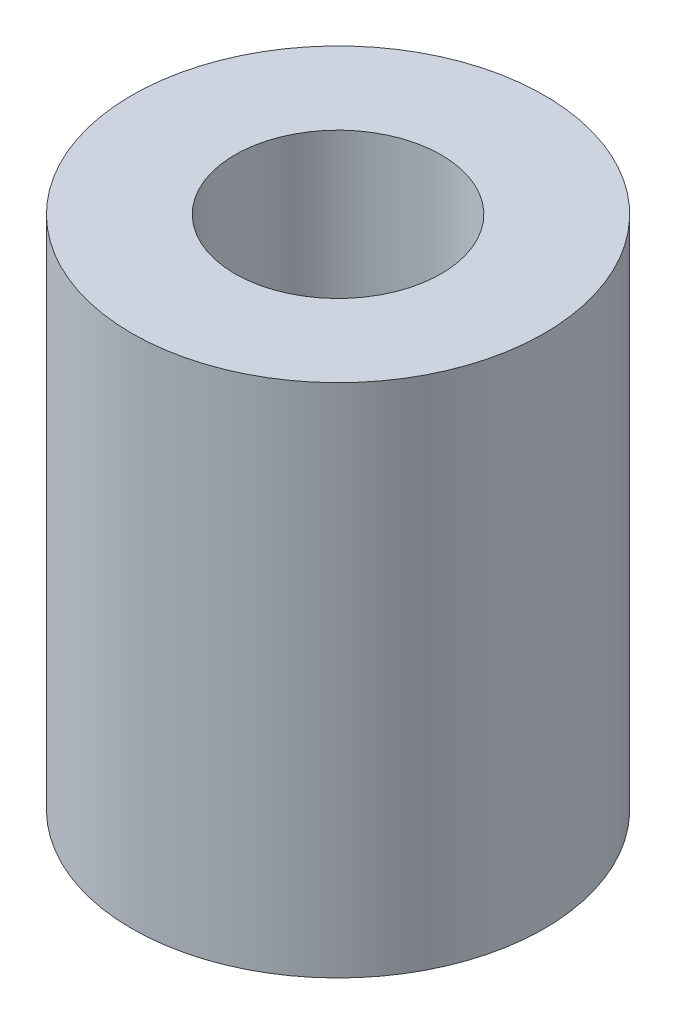
SolidWorks part; units mm, degrees
ref_plane "Спереди" through (0, 0, 0) normal (0, 0, 1) x (1, 0, 0)
ref_plane "Сверху" through (0, 0, 0) normal (0, 1, 0) x (1, 0, 0)
ref_plane "Справа" through (0, 0, 0) normal (1, 0, 0) x (0, 0, -1)
sketch "Эскиз1" plane through (0, 0, 0) normal (0, 1, 0) x (1, 0, 0)
  circle A0 centre (0, 0) radius 10
  circle A1 centre (0, 0) radius 5
  dimension "D1" = 20
  dimension "D2" = 10
extrude "Бобышка-Вытянуть1" add sketch "Эскиз1" along normal blind 25
